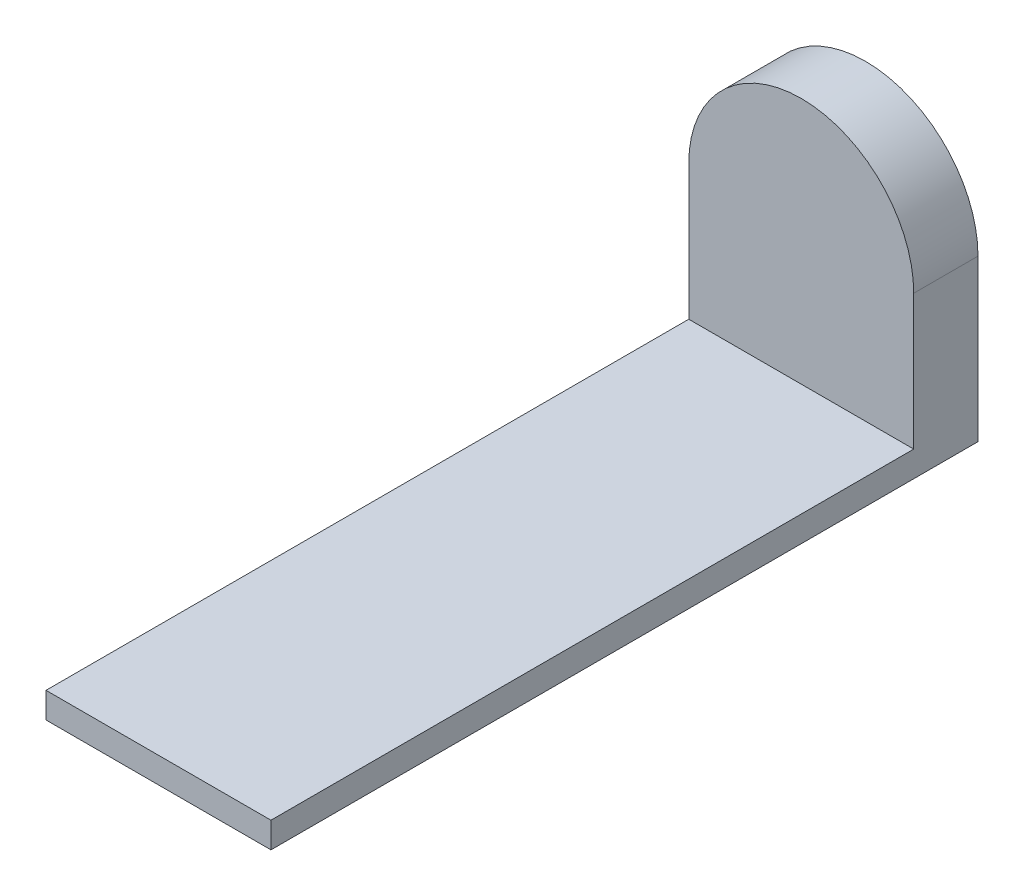
SolidWorks part; units mm, degrees
ref_plane "前视基准面" through (0, 0, 0) normal (0, 0, 1) x (1, 0, 0)
ref_plane "上视基准面" through (0, 0, 0) normal (0, 1, 0) x (1, 0, 0)
ref_plane "右视基准面" through (0, 0, 0) normal (1, 0, 0) x (0, 0, -1)
other "Configuration Table"
sketch "草图1" plane through (0, 0, 0) normal (0, 0, 1) x (1, 0, 0)
  line L0 (-17.5, 0) -> (-17.5, -25)
  line L1 (-17.5, -25) -> (17.5, -25)
  line L2 (17.5, -25) -> (17.5, 0)
  arc A0 (17.5, 0) -> (-17.5, 0) centre (0, 0) ccw
  dimension "D1" = 35
  dimension "D2" = 25
extrude "凸台-拉伸1" add sketch "草图1" along normal blind 10
sketch "草图2" plane through (0, 0, 10) normal (0, 0, 1) x (1, 0, 0)
  line L0 (-17.5, 0) -> (-17.5, -25) construction
  line L1 (-17.5, -21) -> (17.5, -21)
  line L2 (-17.5, -21) -> (-17.5, -25)
  line L3 (-17.5, -25) -> (17.5, -25)
  line L4 (17.5, -21) -> (17.5, -25)
  dimension "D1" = 4
extrude "凸台-拉伸2" add sketch "草图2" along normal blind 100
